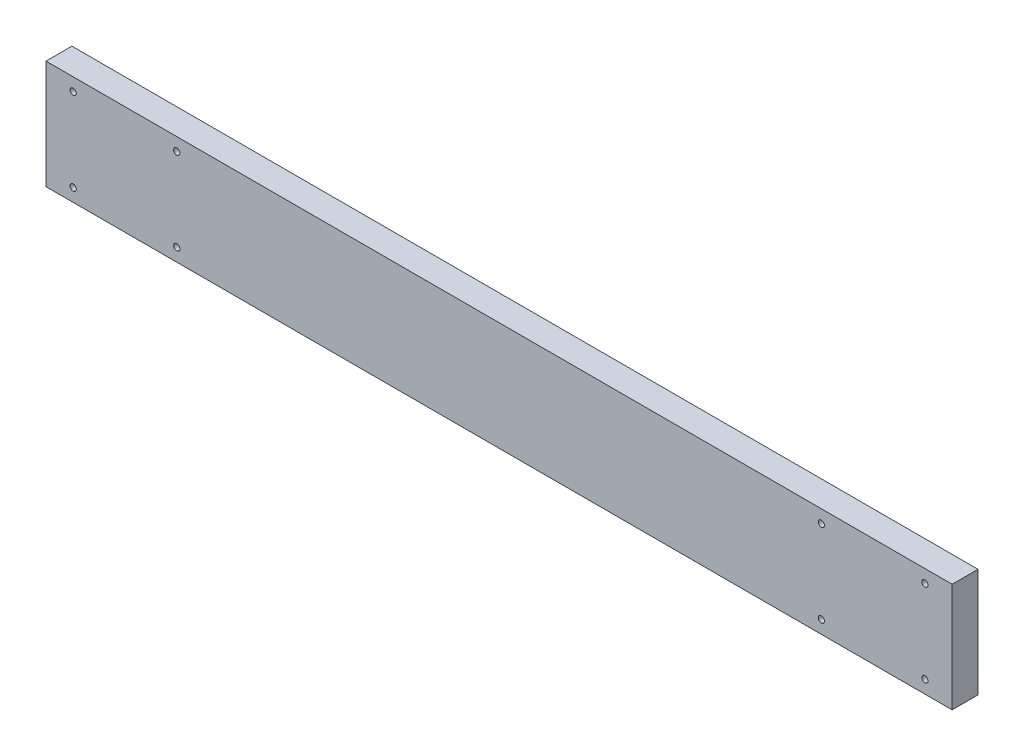
SolidWorks part; units mm, degrees
ref_plane "Front Plane" through (0, 0, 0) normal (0, 0, 1) x (1, 0, 0)
ref_plane "Top Plane" through (0, 0, 0) normal (0, 1, 0) x (1, 0, 0)
ref_plane "Right Plane" through (0, 0, 0) normal (1, 0, 0) x (0, 0, -1)
sketch "Sketch1" plane through (0, 0, 0) normal (0, 0, 1) x (1, 0, 0)
  line L1 (-175, -21.01) -> (175, -21.01)
  line L2 (-175, -21.01) -> (-175, 21.01)
  line L3 (-175, 21.01) -> (175, 21.01)
  line L4 (175, -21.01) -> (175, 21.01)
  line L5 (-175, -21.01) -> (175, 21.01) construction
  line L6 (-175, 21.01) -> (175, -21.01) construction
  point P0 (0, 0)
  dimension "D1" = 42.02
  dimension "D2" = 350
extrude "Boss-Extrude1" add sketch "Sketch1" along normal blind 10
hole_wizard "M2 Clearance Hole1" positions "Sketch2" profile "Sketch3" hole size "M2" standard "ANSI Metric" end condition through all
sketch "Sketch2" plane through (0, 0, 10) normal (0, 0, 1) x (1, 0, 0)
  line L0 (175, 21.01) -> (-175, 21.01) construction
  line L1 (-175, 21.01) -> (-175, -21.01) construction
  line L2 (-175, 0) -> (175, 0) construction
  line L3 (175, -21.01) -> (175, 21.01) construction
  line L5 (0, 21.01) -> (0, -21.01) construction
  line L6 (-175, -21.01) -> (175, -21.01) construction
  point P0 (-164.5, 16.01)
  point P2 (-124.5, 16.01)
  point P15 (-124.5, -16.01)
  point P16 (-164.5, -16.01)
  point P21 (164.5, -16.01)
  point P22 (124.5, -16.01)
  point P23 (124.5, 16.01)
  point P24 (164.5, 16.01)
  dimension "D1" = 5
  dimension "D2" = 10.5
  dimension "D3" = 50.5
sketch "Sketch3" plane through (-164.5, 16.01, 10) normal (1, 0, 0) x (0, -1, 0)
  line L0 (0, 0) -> (0, 10)
  line L1 (0, 10) -> (1.2, 10)
  line L2 (1.2, 10) -> (1.2, 0)
  line L5 (1.2, 0) -> (0, 0)
  line L11 (0, -6.35) -> (0, 107.95) construction
  dimension "Thru Hole Dia." = 2.4
  dimension "Thru Hole Depth" = 10
